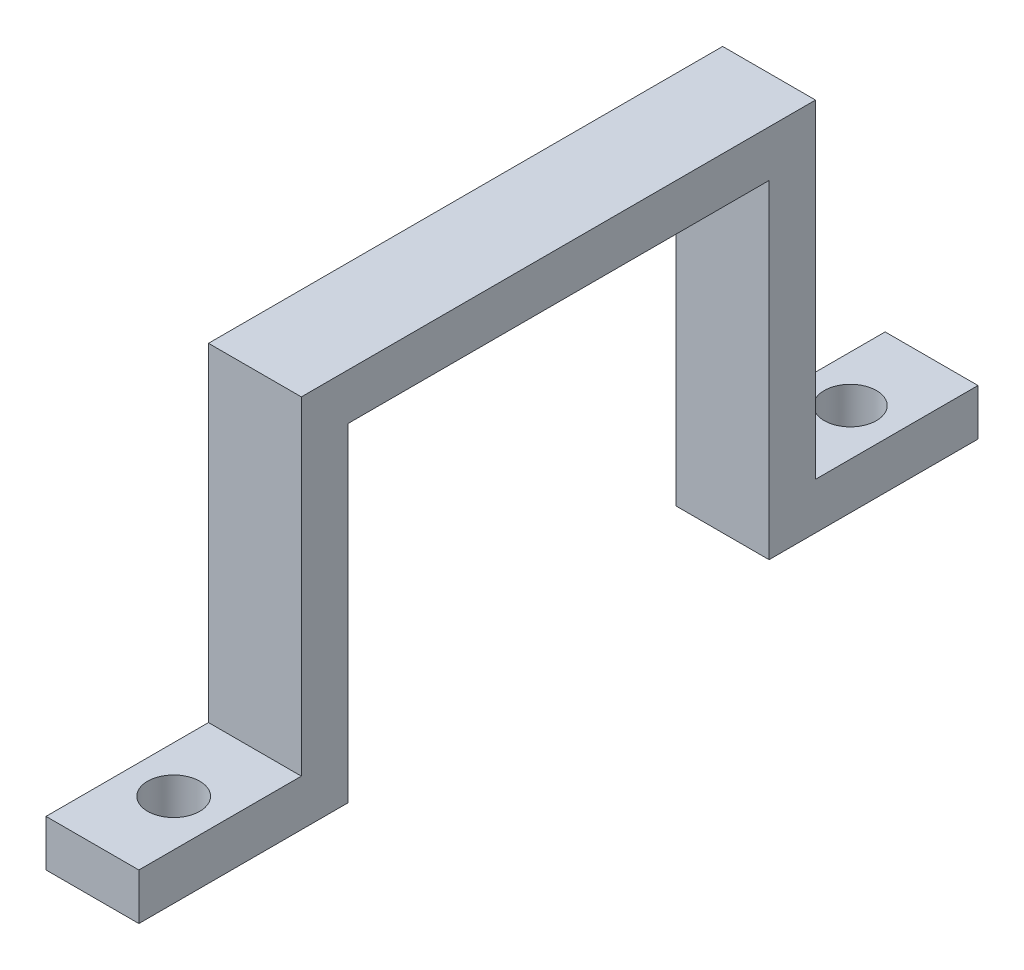
SolidWorks part; units mm, degrees
ref_plane "Front Plane" through (0, 0, 0) normal (0, 0, 1) x (1, 0, 0)
ref_plane "Top Plane" through (0, 0, 0) normal (0, 1, 0) x (1, 0, 0)
ref_plane "Right Plane" through (0, 0, 0) normal (1, 0, 0) x (0, 0, -1)
other "Configuration Table"
sketch "Sketch1" plane through (0, 0, 0) normal (1, 0, 0) x (0, 0, -1)
  line L0 (-36.15, 0) -> (-18.15, 0)
  line L1 (-18.15, 0) -> (-18.15, 28.3)
  line L2 (-18.15, 28.3) -> (18.15, 28.3)
  line L3 (18.15, 28.3) -> (18.15, 0)
  line L4 (18.15, 0) -> (36.15, 0)
  line L5 (36.15, 0) -> (36.15, 4)
  line L6 (36.15, 4) -> (22.15, 4)
  line L7 (22.15, 4) -> (22.15, 32.3)
  line L8 (22.15, 32.3) -> (-22.15, 32.3)
  line L9 (-22.15, 32.3) -> (-22.15, 4)
  line L10 (-22.15, 4) -> (-36.15, 4)
  line L11 (-36.15, 4) -> (-36.15, 0)
extrude "Strap" add sketch "Sketch1" along normal mid plane 8
sketch "Sketch2" plane through (0, 0, 0) normal (0, 1, 0) x (1, 0, 0)
  circle A0 centre (0, 29.15) radius 2.25
  circle A1 centre (0, -29.15) radius 2.25
  dimension "D1" = 4.5
  dimension "D2" = 4.5
extrude "Ear_Holes_M4" cut sketch "Sketch2" along normal blind 5 from offset 0.5
equation "\"Jar_OD\"= 90  'ASSUMED - Part G fallback - jar outer diameter"
equation "\"Jar_H\"= 120  'ASSUMED - Part G fallback - jar height"
equation "\"Pump_L\"= 45  'ASSUMED - Part G fallback"
equation "\"Pump_W\"= 24  'ASSUMED - Part G fallback"
equation "\"Pump_H\"= 33  'ASSUMED - Part G fallback"
equation "\"Pump_Outlet_OD\"= 7.5  'ASSUMED - Part G fallback"
equation "\"Tube_OD\"= 8  'ASSUMED - Part G fallback"
equation "\"Tube_ID\"= 6  'ASSUMED - Part G fallback"
equation "\"TDS_Body_Dia\"= 12  'ASSUMED - Part G fallback"
equation "\"TDS_Wet_Len\"= 45  'ASSUMED - Part G fallback - length in water"
equation "\"DS_Tube_Dia\"= 6  'ASSUMED - Part G fallback"
equation "\"DS_Tube_Len\"= 50  'ASSUMED - Part G fallback"
equation "\"ORP_Body_Dia\"= 12  'ASSUMED - Part G fallback"
equation "\"ORP_Body_Len\"= 150  'ASSUMED - Part G fallback"
equation "\"ORP_Cap_Dia\"= 16  'ASSUMED - Part G fallback"
equation "\"Turb_W\"= 33  'ASSUMED - Part G fallback - head width"
equation "\"Turb_D\"= 28  'ASSUMED - Part G fallback - head depth"
equation "\"Turb_H\"= 30  'ASSUMED - Part G fallback - head height"
equation "\"Turb_Slot_W\"= 10  'ASSUMED - Part G fallback - slot width"
equation "\"Flow_L\"= 62  'ASSUMED - Part G fallback YF-S201"
equation "\"Flow_W\"= 36  'ASSUMED - Part G fallback"
equation "\"Flow_H\"= 35  'ASSUMED - Part G fallback"
equation "\"Thread_G12_OD\"= 20.955  'ASSUMED - Part G fallback thread G1/2 (major diameter)"
equation "\"Valve_L\"= 75  'ASSUMED - Part G fallback"
equation "\"Valve_W\"= 45  'ASSUMED - Part G fallback"
equation "\"Valve_H\"= 60  'ASSUMED - Part G fallback"
equation "\"Tee_L\"= 40  'ASSUMED - Part G fallback - overall length"
equation "\"Tee_Branch_L\"= 25  'ASSUMED - Part G fallback"
equation "\"Tee_OD\"= 12  'ASSUMED - Part G fallback"
equation "\"LED_Board_L\"= 20  'ASSUMED - Part G fallback"
equation "\"LED_Board_W\"= 20  'ASSUMED - Part G fallback - LED at centre"
equation "\"GUVA_L\"= 20  'ASSUMED - Part G fallback"
equation "\"GUVA_W\"= 12  'ASSUMED - Part G fallback - sensor at centre"
equation "\"Reed_L\"= 27  'ASSUMED - Part G fallback MC-38 half"
equation "\"Reed_W\"= 14  'ASSUMED - Part G fallback"
equation "\"Reed_H\"= 8  'ASSUMED - Part G fallback"
equation "\"ESP_L\"= 51  'ASSUMED - Part G fallback"
equation "\"ESP_W\"= 28  'ASSUMED - Part G fallback"
equation "\"TFT_L\"= 58  'ASSUMED - Part G fallback - board"
equation "\"TFT_W\"= 35  'ASSUMED - Part G fallback - board"
equation "\"TFT_Win_L\"= 35  'ASSUMED - Part G fallback - visible window"
equation "\"TFT_Win_W\"= 28  'ASSUMED - Part G fallback - visible window"
equation "\"Relay_L\"= 50  'ASSUMED - Part G fallback"
equation "\"Relay_W\"= 26  'ASSUMED - Part G fallback"
equation "\"Relay_H\"= 19  'ASSUMED - Part G fallback"
equation "\"Mosfet_L\"= 34  'ASSUMED - Part G fallback"
equation "\"Mosfet_W\"= 17  'ASSUMED - Part G fallback"
equation "\"Mosfet_H\"= 12  'ASSUMED - Part G fallback"
equation "\"TDS_Board_L\"= 42  'ASSUMED - Part G fallback"
equation "\"TDS_Board_W\"= 32  'ASSUMED - Part G fallback"
equation "\"Turb_Board_L\"= 38  'ASSUMED - Part G fallback"
equation "\"Turb_Board_W\"= 28  'ASSUMED - Part G fallback"
equation "\"BNC_Thread_Dia\"= 9.5  'ASSUMED - Part G fallback"
equation "\"Plate_L\"= 420  'ASSUMED - Part G fallback"
equation "\"Plate_W\"= 297  'ASSUMED - Part G fallback"
equation "\"Plate_T\"= 6  'ASSUMED - Part G fallback"
equation "\"Booster_L\"= 150  'ASSUMED - Part G fallback - booster pump"
equation "\"Booster_W\"= 95  'ASSUMED - Part G fallback"
equation "\"Booster_H\"= 100  'ASSUMED - Part G fallback"
equation "\"PTube_OD\"= 6.35  'ASSUMED - Part G fallback - product tube 1/4 inch"
equation "\"Qz_Out\"= 12  'ASSUMED - Part G fallback - quartz channel outside square"
equation "\"Qz_Path\"= 10  'ASSUMED - Part G fallback - quartz channel inside light path"
equation "\"Qz_L\"= 40  'ASSUMED - Part G fallback - quartz channel length"
equation "\"LED860_Dia\"= 5  'ASSUMED - Part G fallback - 860 nm LED"
equation "\"BPW_L\"= 5.4  'ASSUMED - Part G fallback - BPW34"
equation "\"BPW_W\"= 4.3  'ASSUMED - Part G fallback - BPW34"
equation "\"Cart_Dia\"= 50  'ASSUMED - Part G fallback - sediment and pre-carbon cartridges"
equation "\"Cart_L\"= 255  'ASSUMED - Part G fallback"
equation "\"UF_Dia\"= 50  'ASSUMED - Part G fallback - UF cartridge"
equation "\"UF_L\"= 260  'ASSUMED - Part G fallback"
equation "\"RO_Dia\"= 62  'ASSUMED - Part G fallback - RO membrane housing"
equation "\"RO_L\"= 300  'ASSUMED - Part G fallback"
equation "\"UVC_Dia\"= 40  'ASSUMED - Part G fallback - UV-C chamber"
equation "\"UVC_L\"= 300  'ASSUMED - Part G fallback"
equation "\"Tank_W\"= 260  'ASSUMED - Part G fallback - storage tank"
equation "\"Tank_D\"= 160  'ASSUMED - Part G fallback"
equation "\"Tank_H\"= 300  'ASSUMED - Part G fallback"
equation "\"Cab_W\"= 400  'ASSUMED - Part G fallback - purifier cabinet"
equation "\"Cab_D\"= 270  'ASSUMED - Part G fallback"
equation "\"Cab_H\"= 560  'ASSUMED - Part G fallback"
equation "\"ORP_Board_L\"= 40  'ASSUMED - Part G fallback - ORP buffer board"
equation "\"ORP_Board_W\"= 30  'ASSUMED - Part G fallback"
equation "\"Opt_Board_L\"= 50  'ASSUMED - Part G fallback - optical front-end board"
equation "\"Opt_Board_W\"= 40  'ASSUMED - Part G fallback"
equation "\"Buck_L\"= 43  'ASSUMED - Part G fallback - 12 V to 5 V buck module"
equation "\"Buck_W\"= 21  'ASSUMED - Part G fallback"
equation "\"Buck_H\"= 14  'ASSUMED - Part G fallback"
equation "\"BB_L\"= 165  'ASSUMED - Part G fallback - breadboard (As_Built_R3 only)"
equation "\"BB_W\"= 55  'ASSUMED - Part G fallback"
equation "\"BB_H\"= 10  'ASSUMED - Part G fallback"
equation "\"Cuv_W\"= 12.5  'ASSUMED - old R3 cuvette (station suppressed in SS4)"
equation "\"Cuv_D\"= 12.5  'ASSUMED - old R3 cuvette (station suppressed in SS4)"
equation "\"Cuv_H\"= 45  'ASSUMED - old R3 cuvette (station suppressed in SS4)"
equation "\"Probe_Clr\"= 0.3  'DESIGN VALUE - Part C rule 3 - printed probe hole = diameter + 0.3"
equation "\"Label_H\"= 0.6  'DESIGN VALUE - Part D - raised label height"
